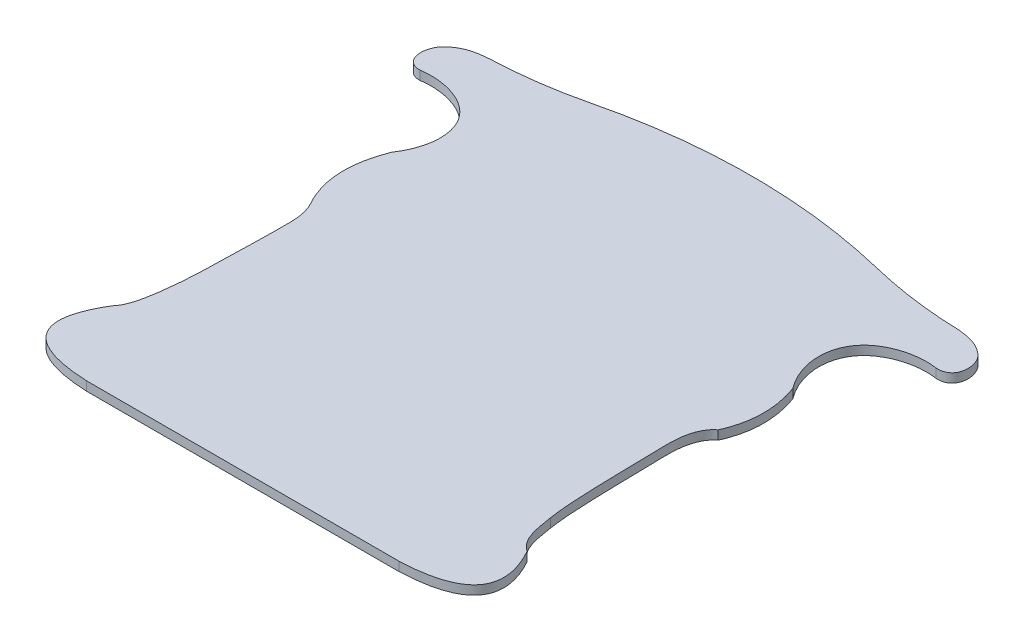
SolidWorks part; units mm, degrees
ref_plane "前视基准面" through (0, 0, 0) normal (0, 0, 1) x (1, 0, 0)
ref_plane "上视基准面" through (0, 0, 0) normal (0, 1, 0) x (1, 0, 0)
ref_plane "右视基准面" through (0, 0, 0) normal (1, 0, 0) x (0, 0, -1)
other "Configuration Table"
sketch "草图1" plane through (0, 0, 0) normal (0, 1, 0) x (1, 0, 0)
  line L0 (92.6988, -85.2377) -> (-93.6497, -85.2377)
  line L1 (-93.6497, 74.7623) -> (-83.5417, 74.7623)
  line L2 (82.5908, 74.7623) -> (92.6988, 74.7623)
  line L3 (0, 92.1982) -> (0, -91.4375) construction
  arc A0 (92.6988, -85.2377) -> (116.9403, -66.3489) centre (92.6988, -60.2377) ccw
  arc A1 (-117.8913, -66.3489) -> (-93.6497, -85.2377) centre (-93.6497, -60.2377) ccw
  arc A2 (-117.8913, 55.8734) -> (-117.8913, -66.3489) centre (124.5245, -5.2377) ccw
  arc A3 (-93.6497, 74.7623) -> (-117.8913, 55.8734) centre (-93.6497, 49.7623) ccw
  arc A4 (-83.5417, 74.7623) -> (-47.9419, 79.048) centre (-83.5417, 224.7623) ccw
  arc A5 (46.9909, 79.048) -> (-47.9419, 79.048) centre (-0.4755, -115.2377) ccw
  arc A6 (46.9909, 79.048) -> (82.5908, 74.7623) centre (82.5908, 224.7623) ccw
  arc A7 (116.9403, 55.8734) -> (92.6988, 74.7623) centre (92.6988, 49.7623) ccw
  arc A8 (116.9403, -66.3489) -> (116.9403, 55.8734) centre (-125.4755, -5.2377) ccw
  spline S0 degree 3 poles (64.5897, 21.3157) (58.8933, 53.6548) (81.1888, 62.0638) (93.681, 58.428) (100.4929, 49.4656) (99.9342, 39.5153) (101.6725, 28.2144) (100.4316, 15.2254) (64.5897, 21.3157) (58.8933, 53.6548) (81.1888, 62.0638) knots -0.58846 -0.515599 -0.249223 0 0.116916 0.219737 0.24839 0.386216 0.41154 0.484401 0.750777 1 1.116916 1.219737 1.24839 only from (67.2947, 54.7879) to (67.2947, 54.7879)
  spline S1 degree 3 poles (64.687, -47.3353) (64.8217, -48.2289) (65.0931, -50.0157) (65.5152, -52.2347) (65.9467, -53.9911) (66.3371, -55.2913) (66.8233, -56.5577) (67.4334, -57.7687) (68.1865, -58.8947) (69.0895, -59.905) (69.947, -60.641) (70.6816, -61.1664) (71.2536, -61.53) (71.8431, -61.8643) (72.4473, -62.1712) (73.0639, -62.4524) (73.6907, -62.7101) (74.3261, -62.9462) (75.1827, -63.2347) (76.268, -63.5511) (77.3657, -63.821) (78.2486, -64.0147) (78.913, -64.1493) (79.5794, -64.2738) (80.4705, -64.4251) (81.3658, -64.5518) (82.2655, -64.6426) (82.9422, -64.6885) (83.6202, -64.7066) (84.2983, -64.6907) (84.9748, -64.6341) (85.6447, -64.5278) (86.3011, -64.3622) (86.9358, -64.1278) (87.5379, -63.8174) (88.002, -63.4961) (88.3462, -63.2048) (88.6716, -62.8926) (89.1903, -62.2962) (89.7891, -61.332) (90.3306, -60.0879) (90.7489, -58.7968) (91.0907, -57.4847) (91.3838, -56.1612) (91.6067, -55.0538) (91.7797, -54.1671) (91.908, -53.5018) (92.0362, -52.8365) (92.208, -51.9497) (92.4262, -50.8418) (92.7839, -49.0709) (93.2395, -46.859) (93.7643, -44.2003) (94.2384, -41.5323) (94.653, -38.8546) (95.0115, -36.1689) (95.2947, -33.7012) (95.4755, -31.9038) (95.6227, -30.3299) (95.8376, -27.8552) (96.1019, -24.2511) (96.3526, -20.4197) (96.5599, -17.2646) (96.7472, -14.5611) (96.8771, -12.7592) (96.9421, -11.8583) knots 0 0 0 0 0.03125 0.0625 0.078125 0.09375 0.109375 0.125 0.140625 0.15625 0.171875 0.179688 0.1875 0.195312 0.203125 0.210938 0.21875 0.226562 0.234375 0.25 0.265625 0.273438 0.28125 0.289062 0.296875 0.3125 0.320312 0.328125 0.335938 0.34375 0.351562 0.359375 0.367188 0.375 0.382812 0.390625 0.394531 0.398438 0.40625 0.421875 0.4375 0.453125 0.46875 0.484375 0.5 0.507812 0.515625 0.523438 0.53125 0.546875 0.5625 0.59375 0.625 0.65625 0.6875 0.71875 0.75 0.773438 0.78125 0.804688 0.859375 0.90625 0.9375 0.96875 1 1 1 1
  spline S2 degree 3 poles (96.9421, -11.8583) (96.9666, -11.7379) (97.0154, -11.4971) (97.1077, -11.0144) (97.2406, -10.164) (97.3105, -9.181) (97.2812, -8.1993) (97.2049, -7.4666) (97.0712, -6.7422) (96.8782, -6.0316) (96.625, -5.3403) (96.2083, -4.4522) (95.2784, -3.0018) (93.8538, -1.6261) (92.2361, -0.5067) (90.9554, 0.2248) (89.6276, 0.8642) (88.2677, 1.4301) (86.8858, 1.943) (85.7236, 2.344) (84.7919, 2.6596) (84.0934, 2.8963) (83.5123, 3.0957) (83.0484, 3.2575) (82.5851, 3.4208) (82.0073, 3.628) (81.4312, 3.8399) (80.9715, 4.0124) (80.5125, 4.1867) (79.9398, 4.4077) (79.2537, 4.6762) (78.5682, 4.9463) (77.8822, 5.2159) (77.1948, 5.4824) (76.505, 5.743) (75.8115, 5.9937) (75.1131, 6.2296) (74.4087, 6.4458) (73.6971, 6.637) (72.9774, 6.7976) (72.3705, 6.8994) (71.8819, 6.9568) (71.5145, 6.9866) (71.1465, 7.0017) (70.7785, 7.001) (70.4111, 6.983) (70.0451, 6.9465) (69.6818, 6.8905) (69.2024, 6.7884) (68.6159, 6.6073) (67.9441, 6.3045) (67.1056, 5.7925) (66.1888, 4.9681) (65.4433, 3.9848) (64.9387, 3.1426) (64.6028, 2.4865) (64.3064, 1.8118) (64.0465, 1.1225) (63.8212, 0.4211) (63.6284, -0.2901) (63.4661, -1.0088) (63.3324, -1.733) (63.2249, -2.4613) (63.1129, -3.4366) (63.0425, -4.4168) (63.0027, -5.3994) (62.9854, -6.1369) (62.9779, -6.8746) (62.9778, -7.6121) (62.9829, -8.3493) (62.9915, -9.0863) (63.0022, -9.8231) (63.0185, -10.8054) (63.0408, -12.0331) (63.1175, -15.9614) (63.21, -19.889) (63.3048, -23.8167) (63.3467, -25.535) (63.3833, -27.0079) (63.421, -28.4808) (63.4664, -30.1992) (63.537, -32.6539) (63.6494, -35.5988) (63.8064, -38.5417) (64.0216, -41.4805) (64.2603, -43.9243) (64.4938, -45.8747) (64.6226, -46.8484) (64.687, -47.3353) knots 0 0 0 0 0.003906 0.007812 0.015625 0.03125 0.039062 0.046875 0.054688 0.0625 0.070312 0.078125 0.09375 0.125 0.140625 0.15625 0.171875 0.1875 0.203125 0.21875 0.226562 0.234375 0.242188 0.246094 0.25 0.257812 0.265625 0.269531 0.273438 0.28125 0.289062 0.296875 0.304688 0.3125 0.320312 0.328125 0.335938 0.34375 0.351562 0.359375 0.367188 0.371094 0.375 0.378906 0.382812 0.386719 0.390625 0.394531 0.398438 0.40625 0.414062 0.421875 0.4375 0.453125 0.460938 0.46875 0.476562 0.484375 0.492188 0.5 0.507812 0.515625 0.523438 0.53125 0.546875 0.554688 0.5625 0.570312 0.578125 0.585938 0.59375 0.601562 0.609375 0.625 0.640625 0.734375 0.75 0.765625 0.789062 0.796875 0.8125 0.84375 0.875 0.90625 0.9375 0.96875 0.984375 1 1 1 1
  spline S3 degree 3 poles (-65.0216, 21.3157) (-59.3252, 53.6548) (-81.6207, 62.0638) (-94.1128, 58.428) (-100.9248, 49.4656) (-100.3661, 39.5153) (-102.1044, 28.2144) (-100.8634, 15.2254) (-65.0216, 21.3157) (-59.3252, 53.6548) (-81.6207, 62.0638) knots -0.58846 -0.515599 -0.249223 0 0.116916 0.219737 0.24839 0.386216 0.41154 0.484401 0.750777 1 1.116916 1.219737 1.24839 only from (-67.7265, 54.7879) to (-67.7265, 54.7879)
  spline S4 degree 3 poles (-97.893, -11.8583) (-97.7619, -13.6601) (-97.5032, -17.264) (-97.159, -22.673) (-96.7806, -28.0808) (-96.2936, -33.479) (-95.7417, -37.9618) (-95.1882, -41.5321) (-94.7152, -44.2003) (-94.2785, -46.416) (-93.9177, -48.1863) (-93.646, -49.5138) (-93.3776, -50.8419) (-93.1157, -52.1713) (-92.8587, -53.5018) (-92.645, -54.6107) (-92.4684, -55.4967) (-92.3314, -56.1603) (-92.1876, -56.8225) (-92.0344, -57.4826) (-91.8694, -58.1402) (-91.6897, -58.7942) (-91.5237, -59.3348) (-91.3785, -59.7632) (-91.224, -60.1883) (-91.0115, -60.7123) (-90.719, -61.3241) (-90.3823, -61.9122) (-90.0591, -62.3748) (-89.7722, -62.7226) (-89.5424, -62.9708) (-89.298, -63.2047) (-89.0394, -63.4228) (-88.7676, -63.6237) (-88.3886, -63.8675) (-87.8871, -64.1254) (-87.2524, -64.3604) (-86.377, -64.5828) (-85.2497, -64.7108) (-83.8913, -64.6999) (-82.54, -64.5799) (-81.1975, -64.3925) (-80.0856, -64.1938) (-79.1997, -64.0139) (-78.3164, -63.8208) (-77.4381, -63.6056) (-76.5676, -63.3617) (-75.9194, -63.1629) (-75.277, -62.9463) (-74.6415, -62.71) (-74.0145, -62.4521) (-73.1919, -62.0768) (-72.1945, -61.5439) (-71.0691, -60.7879) (-70.0402, -59.905) (-69.2882, -59.0631) (-68.761, -58.3315) (-68.2825, -57.5667) (-67.876, -56.7595) (-67.5321, -55.9243) (-67.3018, -55.2866) (-67.0951, -54.6401) (-66.8462, -53.7698) (-66.5753, -52.6727) (-66.2981, -51.3466) (-66.0564, -50.0135) (-65.8399, -48.6756) (-65.7052, -47.7821) (-65.6379, -47.3353) knots 0 0 0 0 0.0625 0.125 0.1875 0.25 0.3125 0.34375 0.375 0.40625 0.421875 0.4375 0.453125 0.46875 0.484375 0.5 0.507812 0.515625 0.523438 0.53125 0.539062 0.546875 0.554688 0.558594 0.5625 0.570312 0.578125 0.585938 0.59375 0.597656 0.601562 0.605469 0.609375 0.613281 0.617188 0.625 0.632812 0.640625 0.65625 0.671875 0.6875 0.703125 0.71875 0.726562 0.734375 0.75 0.757812 0.765625 0.773438 0.78125 0.789062 0.796875 0.8125 0.828125 0.84375 0.859375 0.867188 0.875 0.890625 0.898438 0.90625 0.914062 0.921875 0.9375 0.953125 0.96875 0.984375 1 1 1 1
  spline S5 degree 3 poles (-65.6379, -47.3353) (-65.3733, -45.3887) (-64.9244, -41.4845) (-64.643, -36.5796) (-64.4902, -32.6539) (-64.375, -28.7264) (-64.2575, -23.8166) (-64.1169, -17.9249) (-64.0098, -13.015) (-63.9477, -9.5777) (-63.9275, -7.6126) (-63.9336, -5.6462) (-64.0177, -3.6813) (-64.2701, -1.7314) (-64.5148, -0.5264) (-64.7717, 0.4223) (-64.9969, 1.1238) (-65.2567, 1.813) (-65.5534, 2.4872) (-65.8335, 3.0336) (-66.0786, 3.4593) (-66.3382, 3.8765) (-66.6911, 4.3802) (-67.6326, 5.5154) (-69.0636, 6.5403) (-70.9915, 6.9946) (-72.4673, 7.0228) (-73.6883, 6.8514) (-74.6479, 6.6369) (-75.3596, 6.4447) (-76.064, 6.2277) (-76.7624, 5.9913) (-77.456, 5.741) (-78.376, 5.3951) (-79.5198, 4.9478) (-80.8902, 4.4063) (-82.2658, 3.879) (-84.1111, 3.2061) (-85.9755, 2.5829) (-87.8357, 1.9421) (-89.2184, 1.4294) (-90.5785, 0.864) (-91.9059, 0.2248) (-93.1858, -0.5064) (-94.3994, -1.3469) (-95.5158, -2.3131) (-96.826, -3.783) (-97.7537, -5.5388) (-98.184, -7.4622) (-98.264, -8.69) (-98.2284, -9.6734) (-98.1681, -10.2856) (-98.0988, -10.7723) (-98.0163, -11.2567) (-97.9429, -11.6178) (-97.893, -11.8583) knots 0 0 0 0 0.0625 0.125 0.15625 0.1875 0.25 0.3125 0.375 0.40625 0.421875 0.4375 0.46875 0.484375 0.5 0.507812 0.515625 0.523438 0.53125 0.539062 0.542969 0.546875 0.554688 0.5625 0.59375 0.609375 0.625 0.640625 0.648438 0.65625 0.664062 0.671875 0.679688 0.6875 0.703125 0.71875 0.734375 0.75 0.78125 0.796875 0.8125 0.828125 0.84375 0.859375 0.875 0.890625 0.90625 0.9375 0.953125 0.96875 0.976562 0.984375 0.988281 0.992188 1 1 1 1
  spline S6 degree 3 poles (-77.9973, 74.8648) (-82.4955, 74.5638) (-85.82, 73.5617) (-92.6291, 67.6687) (-92.0919, 58.6495) (-84.4762, 60.2321) knots 0 0 0 0 0.398409 0.457074 1 1 1 1
  spline S7 degree 2 poles (-67.3189, 31.51) (-73.2653, 16.4011) (-65.9783, 3.284) knots 0 0 0 1 1 1
  spline S8 degree 2 poles (-52.0846, -85.2377) (-85.9872, -83.8462) (-67.8447, -56.659) knots 0 0 0 1 1 1
  spline S9 degree 2 poles (52.0846, -85.2377) (85.9872, -83.8462) (67.8447, -56.659) knots 0 0 0 1 1 1
  spline S10 degree 2 poles (67.3189, 31.51) (73.2653, 16.4011) (65.9783, 3.284) knots 0 0 0 1 1 1
  spline S11 degree 3 poles (77.9973, 74.8648) (82.4955, 74.5638) (85.82, 73.5617) (92.6291, 67.6687) (92.0919, 58.6495) (84.4762, 60.2321) knots 0 0 0 0 0.398409 0.457074 1 1 1 1
  point P49 (0, 0)
  point P63 (0, 0)
extrude "凸台-拉伸1" add sketch "草图1" along normal blind 3
